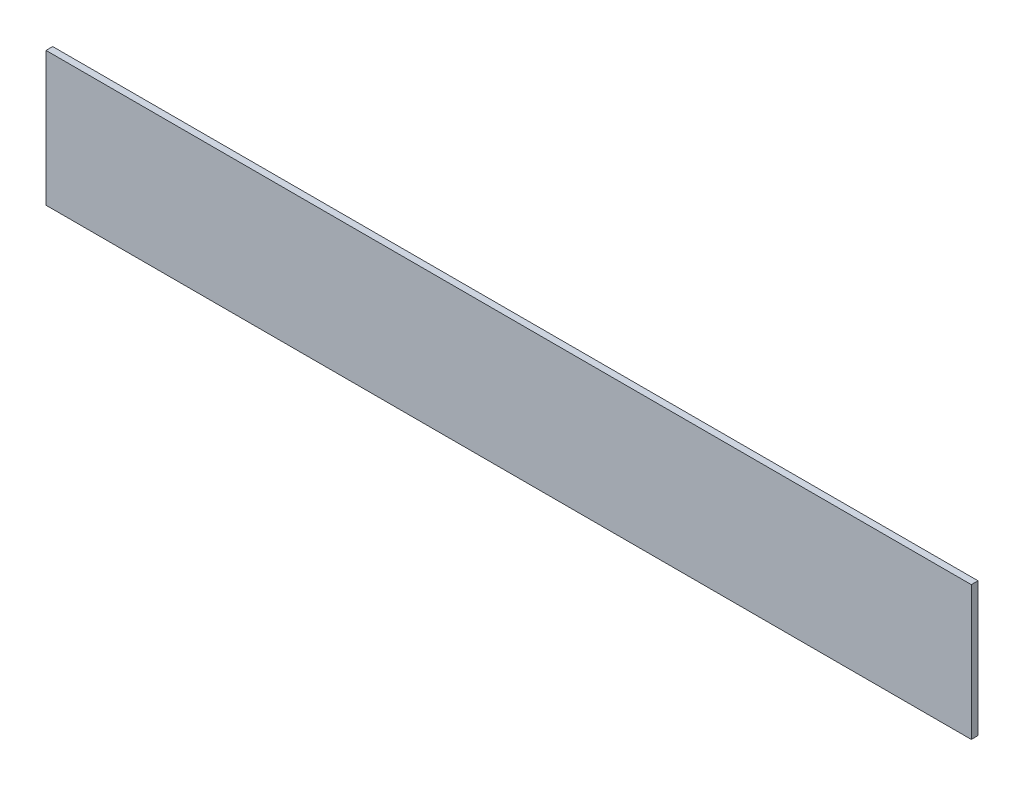
SolidWorks part; units mm, degrees
ref_plane "Front Plane" through (0, 0, 0) normal (0, 0, 1) x (1, 0, 0)
ref_plane "Top Plane" through (0, 0, 0) normal (0, 1, 0) x (1, 0, 0)
ref_plane "Right Plane" through (0, 0, 0) normal (1, 0, 0) x (0, 0, -1)
sketch "Sketch1" plane through (0, 0, 0) normal (0, 0, 1) x (1, 0, 0)
  line L1 (-690, 100) -> (690, 100)
  line L2 (-690, 100) -> (-690, -100)
  line L3 (-690, -100) -> (690, -100)
  line L4 (690, 100) -> (690, -100)
  line L5 (-690, 100) -> (690, -100) construction
  line L6 (-690, -100) -> (690, 100) construction
  point P0 (0, 0)
  dimension "D1" = 1380
extrude "Boss-Extrude1" add sketch "Sketch1" along normal blind 10
